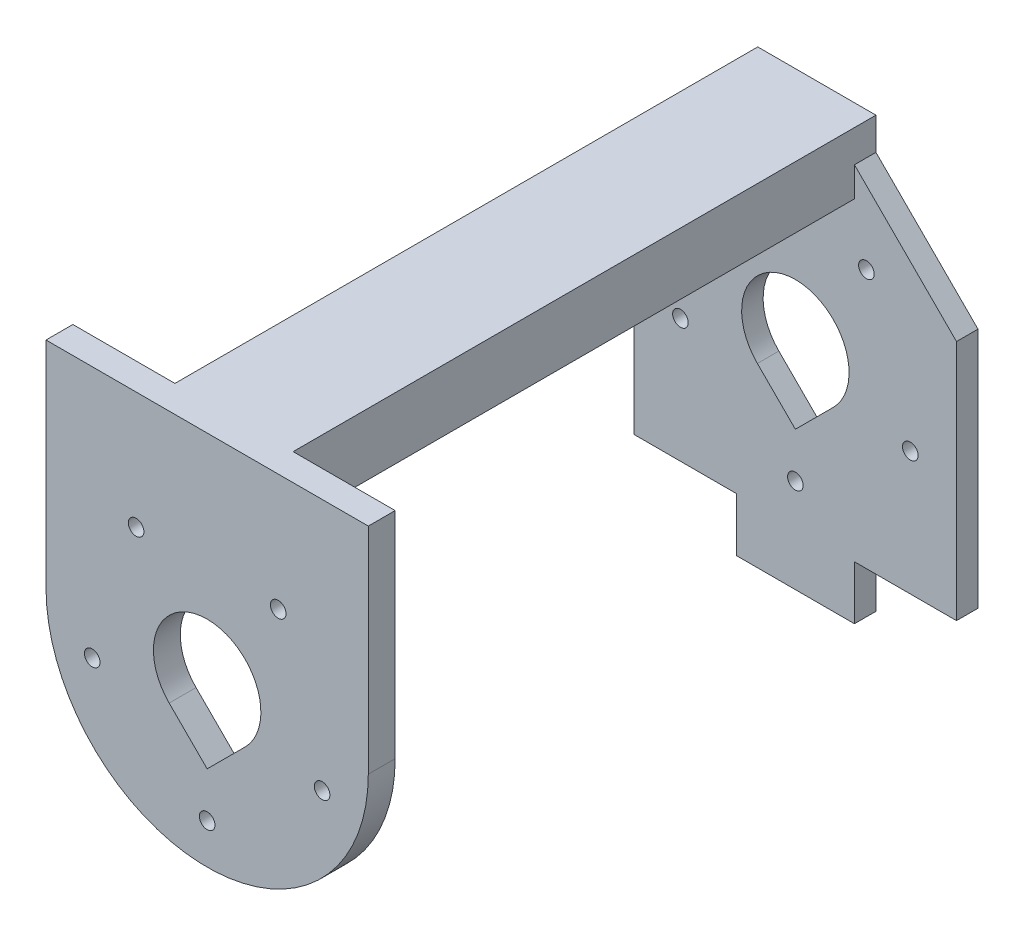
SolidWorks part; units mm, degrees
ref_plane "Front Plane" through (0, 0, 0) normal (0, 0, 1) x (1, 0, 0)
ref_plane "Top Plane" through (0, 0, 0) normal (0, 1, 0) x (1, 0, 0)
ref_plane "Right Plane" through (0, 0, 0) normal (1, 0, 0) x (0, 0, -1)
ref_plane "Plane1" through (0, 0, 384.5) normal (0, 0, 1) x (1, 0, 0)
sketch "Sketch1" plane through (0, 0, 384.5) normal (0, 0, 1) x (1, 0, 0)
  circle A0 centre (300, 300) radius 30
extrude "Boss-Extrude1" add sketch "Sketch1" along normal blind 5
sketch "Sketch2" plane through (0, 0, 384.5) normal (0, 0, 1) x (1, 0, 0)
  line L0 (270, 300) -> (330, 300)
  line L1 (330, 300) -> (330, 340)
  line L2 (330, 340) -> (270, 340)
  line L3 (270, 340) -> (270, 300)
extrude "Boss-Extrude2" add sketch "Sketch2" along normal blind 5
sketch "Sketch3" plane through (0, 0, 384.5) normal (0, 0, 1) x (1, 0, 0)
  line L0 (292.9289, 292.9289) -> (300, 285.8579)
  line L1 (300, 285.8579) -> (307.0711, 292.9289)
  arc A0 (307.0711, 292.9289) -> (292.9289, 292.9289) centre (300, 300) ccw
  circle A1 centre (286.7748, 318.2029) radius 1.45
  circle A2 centre (278.6012, 293.0471) radius 1.45
  circle A3 centre (300, 277.5) radius 1.45
  circle A4 centre (321.3988, 293.0471) radius 1.45
  circle A5 centre (313.2252, 318.2029) radius 1.45
extrude "Cut-Extrude1" cut sketch "Sketch3" along normal blind 5
ref_plane "Plane2" through (0, 0, 276) normal (0, 0, 1) x (1, 0, 0)
sketch "Sketch4" plane through (0, 0, 276) normal (0, 0, 1) x (1, 0, 0)
  line L0 (289, 340) -> (311, 340)
  line L1 (311, 340) -> (311, 334)
  line L2 (311, 334) -> (330, 315)
  line L3 (330, 315) -> (330, 270)
  line L4 (330, 270) -> (311, 270)
  line L5 (311, 270) -> (311, 260)
  line L6 (311, 260) -> (289, 260)
  line L7 (289, 260) -> (289, 270)
  line L8 (289, 270) -> (270, 270)
  line L9 (270, 270) -> (270, 315)
  line L10 (270, 315) -> (289, 334)
  line L11 (289, 334) -> (289, 340)
  line L12 (292.9289, 292.9289) -> (300, 285.8579)
  line L13 (300, 285.8579) -> (307.0711, 292.9289)
  arc A0 (307.0711, 292.9289) -> (292.9289, 292.9289) centre (300, 300) ccw
  circle A1 centre (286.7748, 318.2029) radius 1.45
  circle A2 centre (278.6012, 293.0471) radius 1.45
  circle A3 centre (300, 277.5) radius 1.45
  circle A4 centre (321.3988, 293.0471) radius 1.45
  circle A5 centre (313.2252, 318.2029) radius 1.45
extrude "Boss-Extrude3" add sketch "Sketch4" along normal blind 4
sketch "Sketch5" plane through (0, 0, 276) normal (0, 0, 1) x (1, 0, 0)
  line L0 (289, 328.5) -> (311, 328.5)
  line L1 (311, 328.5) -> (311, 340)
  line L2 (311, 340) -> (289, 340)
  line L3 (289, 340) -> (289, 328.5)
extrude "Boss-Extrude4" add sketch "Sketch5" along normal blind 108.5
